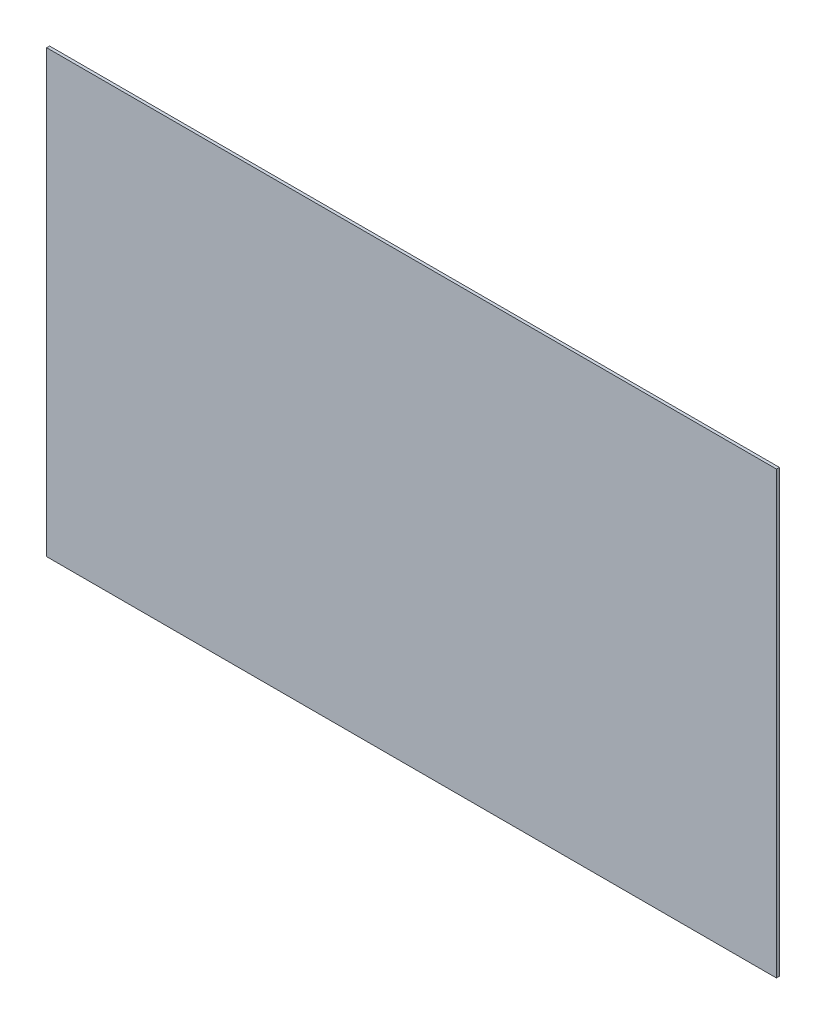
SolidWorks part; units mm, degrees
ref_plane "Front Plane" through (0, 0, 0) normal (0, 0, 1) x (1, 0, 0)
ref_plane "Top Plane" through (0, 0, 0) normal (0, 1, 0) x (1, 0, 0)
ref_plane "Right Plane" through (0, 0, 0) normal (1, 0, 0) x (0, 0, -1)
sketch "Sketch1" plane through (0, 0, 0) normal (0, 0, 1) x (1, 0, 0)
  line L0 (2500, 1510) -> (2500, 0)
  line L1 (2500, 1510) -> (0, 1510)
  line L2 (2500, 0) -> (0, 0)
  line L3 (0, 1510) -> (0, 0)
other "Pen Sketch1" parameters "D1"=69.7562, "D2"=44.2015
extrude "Boss-Extrude1" add sketch "Sketch1" along normal blind 10
